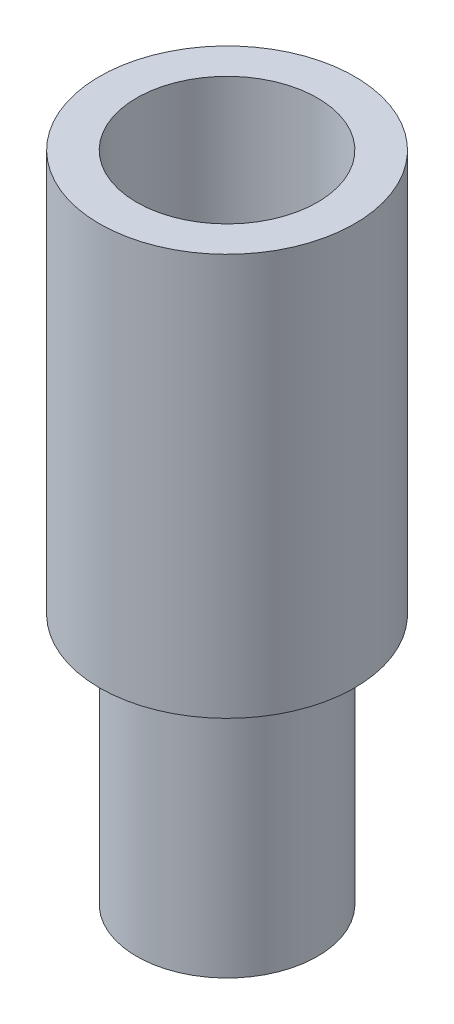
SolidWorks part; units mm, degrees
ref_plane "Front Plane" through (0, 0, 0) normal (0, 0, 1) x (1, 0, 0)
ref_plane "Top Plane" through (0, 0, 0) normal (0, 1, 0) x (1, 0, 0)
ref_plane "Right Plane" through (0, 0, 0) normal (1, 0, 0) x (0, 0, -1)
sketch "Sketch1" plane through (0, 0, 0) normal (0, 1, 0) x (1, 0, 0)
  circle A0 centre (0, 0) radius 12.7
extrude "Boss-Extrude1" add sketch "Sketch1" along normal blind 15
sketch "Sketch2" plane through (0, 0, 0) normal (0, -1, 0) x (1, 0, 0)
  circle A0 centre (0, 0) radius 9
extrude "Boss-Extrude2" add sketch "Sketch2" along normal blind 25
sketch "Sketch3" plane through (0, 15, 0) normal (0, 1, 0) x (1, 0, 0)
  circle A0 centre (0, 0) radius 9
  circle A1 centre (0, 0) radius 12.7
extrude "Boss-Extrude3" add sketch "Sketch3" along normal blind 25
